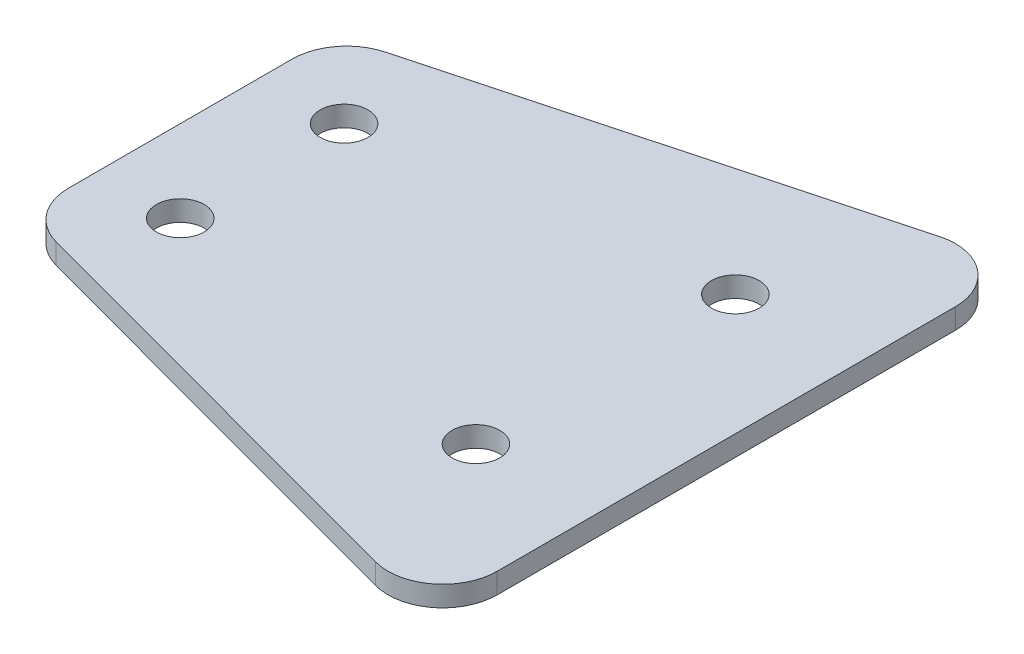
SolidWorks part; units mm, degrees
material "ABS"
ref_plane "Front Plane" through (0, 0, 0) normal (0, 0, 1) x (1, 0, 0)
ref_plane "Top Plane" through (0, 0, 0) normal (0, 1, 0) x (1, 0, 0)
ref_plane "Right Plane" through (0, 0, 0) normal (1, 0, 0) x (0, 0, -1)
sketch "Sketch1" plane through (0, 0, 0) normal (0, 1, 0) x (1, 0, 0)
  line L0 (-40, -16.3661) -> (-40, 16.3661)
  line L1 (-34.0763, 24.092) -> (29.9237, 41.292)
  line L2 (40, 33.5661) -> (40, -33.5661)
  line L3 (40, 0) -> (-40, 0)
  line L4 (-34.0763, -24.092) -> (29.9237, -41.292)
  arc A0 (29.9237, 41.292) -> (40, 33.5661) centre (32, 33.5661) cw
  arc A1 (-40, 16.3661) -> (-34.0763, 24.092) centre (-32, 16.3661) cw
  arc A2 (29.9237, -41.292) -> (40, -33.5661) centre (32, -33.5661) ccw
  arc A3 (-40, -16.3661) -> (-34.0763, -24.092) centre (-32, -16.3661) ccw
  point P8 (0, 0)
  point P10 (40, 44)
  point P13 (-40, 22.5)
  dimension "D4" = 8
  dimension "D1" = 22.5
  dimension "D2" = 44
  dimension "D3" = 80
extrude "Boss-Extrude2" add sketch "Sketch1" along normal mid plane 3 contours L0 A3 L4 A2 L2 L3 | A1 L0 L3 L2 A0 L1
sketch "Sketch3" plane through (0, 1.5, 0) normal (0, 1, 0) x (1, 0, 0)
  line L0 (-40, 0) -> (40, 0) construction
  line L1 (-40, -16.3661) -> (-40, 16.3661) construction
  line L2 (40, 33.5661) -> (40, -33.5661) construction
  circle A1 centre (22.3154, 19) radius 3.5
  circle A2 centre (-28, 12) radius 3.5
  circle A4 centre (22.3154, -19) radius 3.5
  circle A5 centre (-28, -12) radius 3.5
  dimension "D1" = 7
  dimension "D2" = 7
  dimension "D6" = 12
  dimension "D7" = 50.8
  dimension "D8" = 19
  dimension "D9" = 12
extrude "Cut-Extrude1" cut sketch "Sketch3" against normal through all
